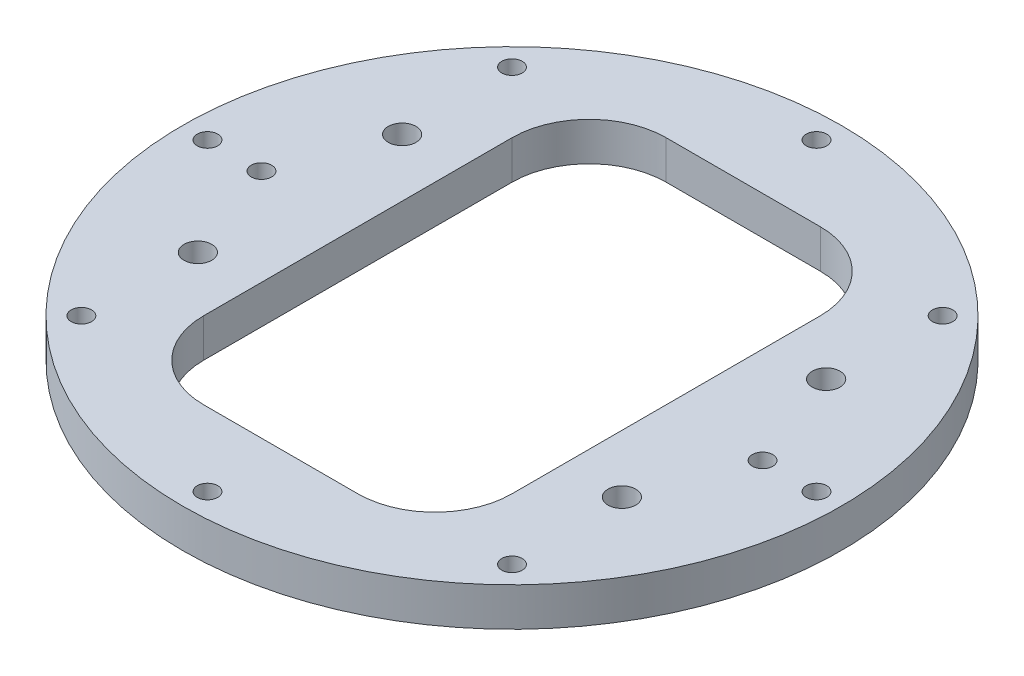
SolidWorks part; units mm, degrees
ref_plane "前视基准面" through (0, 0, 0) normal (0, 0, 1) x (1, 0, 0)
ref_plane "上视基准面" through (0, 0, 0) normal (0, 1, 0) x (1, 0, 0)
ref_plane "右视基准面" through (0, 0, 0) normal (1, 0, 0) x (0, 0, -1)
other "Configuration Table"
sketch "草图1" plane through (0, 0, 0) normal (0, 1, 0) x (1, 0, 0)
  line L0 (-1000, 0) -> (49000, 0) construction
  line L1 (-25, -50) -> (25, -50)
  line L2 (-25, -50) -> (-25, 50)
  line L3 (-25, 50) -> (25, 50)
  line L4 (25, -50) -> (25, 50)
  line L5 (-25, -50) -> (25, 50) construction
  line L6 (-25, 50) -> (25, -50) construction
  line L7 (0, -1000) -> (0, 49000) construction
  line L8 (0, 85.5) -> (0, 72.5)
  line L10 (-40, -50) -> (40, -50)
  line L11 (-40, -50) -> (-40, 50)
  line L12 (-40, 50) -> (40, 50)
  line L13 (40, -50) -> (40, 50)
  line L14 (-40, -50) -> (40, 50) construction
  line L15 (-40, 50) -> (40, -50) construction
  circle A0 centre (0, 0) radius 72.5
  circle A1 centre (0, 0) radius 85.5
  circle A2 centre (0, 79) radius 2.65
  circle A3 centre (55.8614, 55.8614) radius 2.65
  circle A4 centre (79, 0) radius 2.65
  circle A5 centre (55.8614, -55.8614) radius 2.65
  circle A6 centre (0, -79) radius 2.65
  circle A7 centre (-55.8614, -55.8614) radius 2.65
  circle A8 centre (-79, 0) radius 2.65
  circle A9 centre (-55.8614, 55.8614) radius 2.65
  point P33 (0, 0)
  dimension "D1" = 145
  dimension "D5" = 5.3
  dimension "D2" = 50
  dimension "D3" = 100
  dimension "D7" = 80
  dimension "D8" = 100
  dimension "D4" = 13
  dimension "D6" = 8
extrude "凸台-拉伸3" add sketch "草图1" along normal blind 10
sketch "草图10" plane through (0, 10, 0) normal (0, 1, 0) x (1, 0, 0)
  line L0 (0, 0) -> (55, 0)
  line L1 (40, -50) -> (40, 50) construction
  line L2 (55, 0) -> (55, 26.5)
  line L3 (0, -1000) -> (0, 49000) construction
  line L4 (55, 0) -> (65, 0)
  circle A0 centre (55, 26.5) radius 3.6
  circle A1 centre (55, -26.5) radius 3.6
  circle A2 centre (-55, -26.5) radius 3.6
  circle A3 centre (-55, 26.5) radius 3.6
  circle A4 centre (0, 0) radius 72.5
  circle A5 centre (65, 0) radius 2.65
  circle A6 centre (-65, 0) radius 2.65
  dimension "D3" = 7.2
  dimension "D4" = 145
  dimension "D6" = 5.3
  dimension "D1" = 15
  dimension "D2" = 26.5
  dimension "D5" = 10
extrude "切除-拉伸2" cut sketch "草图10" against normal blind 10
sketch "草图11" plane through (0, 10, 0) normal (0, 1, 0) x (1, 0, 0)
  line L1 (-40, -60) -> (40, -60)
  line L2 (-40, -60) -> (-40, 60)
  line L3 (-40, 60) -> (40, 60)
  line L4 (40, -60) -> (40, 60)
  line L5 (-40, -60) -> (40, 60) construction
  line L6 (-40, 60) -> (40, -60) construction
  dimension "D2" = 120
  dimension "D3" = 80
extrude "切除-拉伸3" cut sketch "草图11" against normal blind 10
fillet "圆角1" radius 20 4 edges at (40, 5, 60) (-40, 5, 60) (40, 5, -60) (-40, 5, -60)
